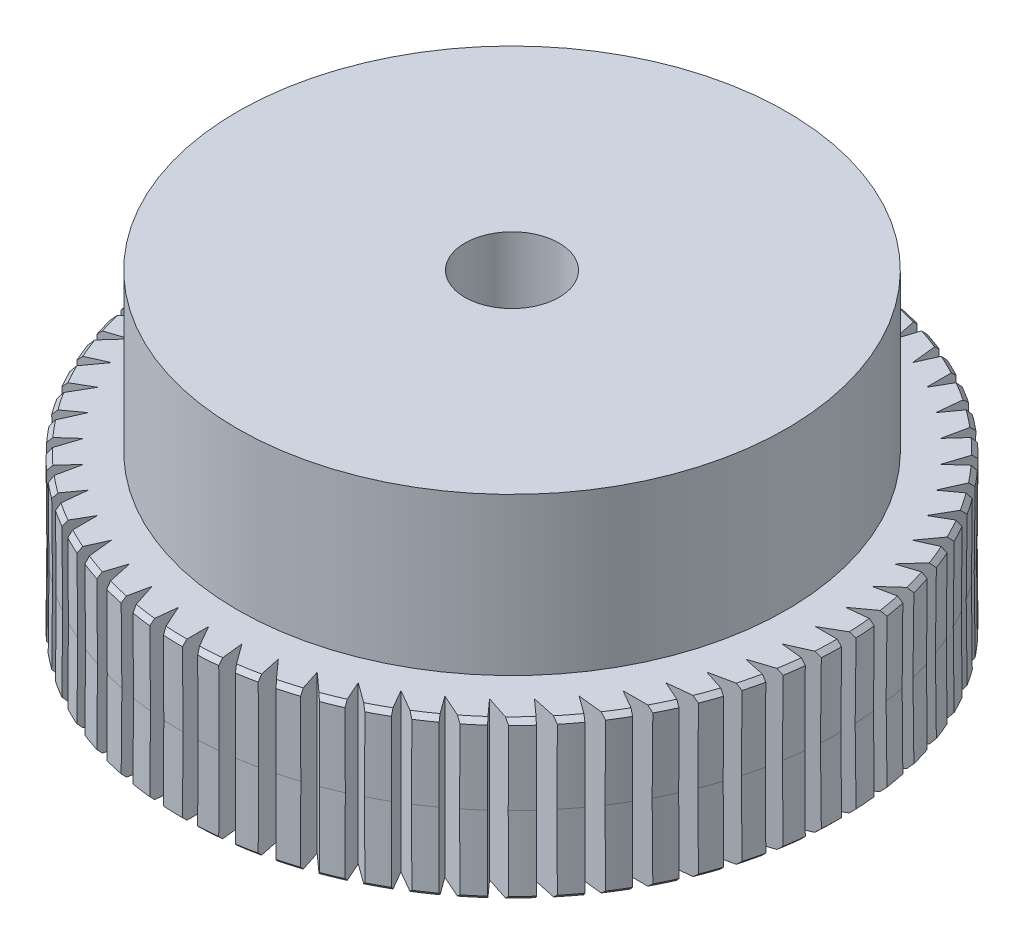
SolidWorks part; units mm, degrees
ref_plane "前视基准面" through (0, 0, 0) normal (0, 0, 1) x (1, 0, 0)
ref_plane "上视基准面" through (0, 0, 0) normal (0, 1, 0) x (1, 0, 0)
ref_plane "右视基准面" through (0, 0, 0) normal (1, 0, 0) x (0, 0, -1)
sketch "草图1" plane through (0, 0, 0) normal (0, 1, 0) x (1, 0, 0)
  circle A0 centre (0, 0) radius 21
  dimension "D1" = 42
extrude "凸台-拉伸1" add sketch "草图1" along normal blind 10
sketch "草图2" plane through (0, 10, 0) normal (0, 1, 0) x (1, 0, 0)
  circle A0 centre (0, 0) radius 17.5
  dimension "D1" = 35
extrude "凸台-拉伸2" add sketch "草图2" along normal blind 10
sketch "草图3" plane through (0, 10, 0) normal (0, 1, 0) x (1, 0, 0)
  line L0 (0, -21) -> (0, -19.3366)
  line L1 (0, -19.3366) -> (0.948, -20.9786)
  line L2 (-2.0212, -19.2306) -> (-1.25, -20.9628)
  line L3 (-2.1951, -20.885) -> (-2.0212, -19.2306)
  line L4 (-4.0203, -18.914) -> (-3.4344, -20.7173)
  line L5 (-4.3661, -20.5411) -> (-4.0203, -18.914)
  line L6 (-5.9753, -18.3902) -> (-5.5811, -20.2448)
  line L7 (-6.4894, -19.9722) -> (-5.9753, -18.3902)
  line L8 (-7.8649, -17.6648) -> (-7.6667, -19.5505)
  line L9 (-8.5415, -19.1845) -> (-7.8649, -17.6648)
  line L10 (-9.6683, -16.746) -> (-9.6683, -18.642)
  line L11 (-10.5, -18.1865) -> (-9.6683, -16.746)
  line L12 (-11.3657, -15.6436) -> (-11.5639, -17.5293)
  line L13 (-12.3435, -16.9894) -> (-11.3657, -15.6436)
  line L14 (-12.9387, -14.3699) -> (-13.3329, -16.2245)
  line L15 (-14.0517, -15.606) -> (-12.9387, -14.3699)
  line L16 (-14.3699, -12.9387) -> (-14.9558, -14.7419)
  line L17 (-15.606, -14.0517) -> (-14.3699, -12.9387)
  line L18 (-15.6436, -11.3657) -> (-16.4148, -13.0979)
  line L19 (-16.9894, -12.3435) -> (-15.6436, -11.3657)
  line L20 (-16.746, -9.6683) -> (-17.694, -11.3103)
  line L21 (-18.1865, -10.5) -> (-16.746, -9.6683)
  line L22 (-17.6648, -7.8649) -> (-18.7793, -9.3988)
  line L23 (-19.1845, -8.5415) -> (-17.6648, -7.8649)
  line L24 (-18.3902, -5.9753) -> (-19.6589, -7.3844)
  line L25 (-19.9722, -6.4894) -> (-18.3902, -5.9753)
  line L26 (-18.914, -4.0203) -> (-20.3231, -5.289)
  line L27 (-20.5411, -4.3661) -> (-18.914, -4.0203)
  line L28 (-19.2306, -2.0212) -> (-20.7646, -3.1357)
  line L29 (-20.885, -2.1951) -> (-19.2306, -2.0212)
  line L30 (-19.3366, 0) -> (-20.9786, -0.948)
  line L31 (-21, 0) -> (-19.3366, 0)
  line L32 (-19.2306, 2.0212) -> (-20.9628, 1.25)
  line L33 (-20.885, 2.1951) -> (-19.2306, 2.0212)
  line L34 (-18.914, 4.0203) -> (-20.7173, 3.4344)
  line L35 (-20.5411, 4.3661) -> (-18.914, 4.0203)
  line L36 (-18.3902, 5.9753) -> (-20.2448, 5.5811)
  line L37 (-19.9722, 6.4894) -> (-18.3902, 5.9753)
  line L38 (-17.6648, 7.8649) -> (-19.5505, 7.6667)
  line L39 (-19.1845, 8.5415) -> (-17.6648, 7.8649)
  line L40 (-16.746, 9.6683) -> (-18.642, 9.6683)
  line L41 (-18.1865, 10.5) -> (-16.746, 9.6683)
  line L42 (-15.6436, 11.3657) -> (-17.5293, 11.5639)
  line L43 (-16.9894, 12.3435) -> (-15.6436, 11.3657)
  line L44 (-14.3699, 12.9387) -> (-16.2245, 13.3329)
  line L45 (-15.606, 14.0517) -> (-14.3699, 12.9387)
  line L46 (-12.9387, 14.3699) -> (-14.7419, 14.9558)
  line L47 (-14.0517, 15.606) -> (-12.9387, 14.3699)
  line L48 (-11.3657, 15.6436) -> (-13.0979, 16.4148)
  line L49 (-12.3435, 16.9894) -> (-11.3657, 15.6436)
  line L50 (-9.6683, 16.746) -> (-11.3103, 17.694)
  line L51 (-10.5, 18.1865) -> (-9.6683, 16.746)
  line L52 (-7.8649, 17.6648) -> (-9.3988, 18.7793)
  line L53 (-8.5415, 19.1845) -> (-7.8649, 17.6648)
  line L54 (-5.9753, 18.3902) -> (-7.3844, 19.6589)
  line L55 (-6.4894, 19.9722) -> (-5.9753, 18.3902)
  line L56 (-4.0203, 18.914) -> (-5.289, 20.3231)
  line L57 (-4.3661, 20.5411) -> (-4.0203, 18.914)
  line L58 (-2.0212, 19.2306) -> (-3.1357, 20.7646)
  line L59 (-2.1951, 20.885) -> (-2.0212, 19.2306)
  line L60 (0, 19.3366) -> (-0.948, 20.9786)
  line L61 (0, 21) -> (0, 19.3366)
  line L62 (2.0212, 19.2306) -> (1.25, 20.9628)
  line L63 (2.1951, 20.885) -> (2.0212, 19.2306)
  line L64 (4.0203, 18.914) -> (3.4344, 20.7173)
  line L65 (4.3661, 20.5411) -> (4.0203, 18.914)
  line L66 (5.9753, 18.3902) -> (5.5811, 20.2448)
  line L67 (6.4894, 19.9722) -> (5.9753, 18.3902)
  line L68 (7.8649, 17.6648) -> (7.6667, 19.5505)
  line L69 (8.5415, 19.1845) -> (7.8649, 17.6648)
  line L70 (9.6683, 16.746) -> (9.6683, 18.642)
  line L71 (10.5, 18.1865) -> (9.6683, 16.746)
  line L72 (11.3657, 15.6436) -> (11.5639, 17.5293)
  line L73 (12.3435, 16.9894) -> (11.3657, 15.6436)
  line L74 (12.9387, 14.3699) -> (13.3329, 16.2245)
  line L75 (14.0517, 15.606) -> (12.9387, 14.3699)
  line L76 (14.3699, 12.9387) -> (14.9558, 14.7419)
  line L77 (15.606, 14.0517) -> (14.3699, 12.9387)
  line L78 (15.6436, 11.3657) -> (16.4148, 13.0979)
  line L79 (16.9894, 12.3435) -> (15.6436, 11.3657)
  line L80 (16.746, 9.6683) -> (17.694, 11.3103)
  line L81 (18.1865, 10.5) -> (16.746, 9.6683)
  line L82 (17.6648, 7.8649) -> (18.7793, 9.3988)
  line L83 (19.1845, 8.5415) -> (17.6648, 7.8649)
  line L84 (18.3902, 5.9753) -> (19.6589, 7.3844)
  line L85 (19.9722, 6.4894) -> (18.3902, 5.9753)
  line L86 (18.914, 4.0203) -> (20.3231, 5.289)
  line L87 (20.5411, 4.3661) -> (18.914, 4.0203)
  line L88 (19.2306, 2.0212) -> (20.7646, 3.1357)
  line L89 (20.885, 2.1951) -> (19.2306, 2.0212)
  line L90 (19.3366, 0) -> (20.9786, 0.948)
  line L91 (21, 0) -> (19.3366, 0)
  line L92 (19.2306, -2.0212) -> (20.9628, -1.25)
  line L93 (20.885, -2.1951) -> (19.2306, -2.0212)
  line L94 (18.914, -4.0203) -> (20.7173, -3.4344)
  line L95 (20.5411, -4.3661) -> (18.914, -4.0203)
  line L96 (18.3902, -5.9753) -> (20.2448, -5.5811)
  line L97 (19.9722, -6.4894) -> (18.3902, -5.9753)
  line L98 (17.6648, -7.8649) -> (19.5505, -7.6667)
  line L99 (19.1845, -8.5415) -> (17.6648, -7.8649)
  line L100 (16.746, -9.6683) -> (18.642, -9.6683)
  line L101 (18.1865, -10.5) -> (16.746, -9.6683)
  line L102 (15.6436, -11.3657) -> (17.5293, -11.5639)
  line L103 (16.9894, -12.3435) -> (15.6436, -11.3657)
  line L104 (14.3699, -12.9387) -> (16.2245, -13.3329)
  line L105 (15.606, -14.0517) -> (14.3699, -12.9387)
  line L106 (12.9387, -14.3699) -> (14.7419, -14.9558)
  line L107 (14.0517, -15.606) -> (12.9387, -14.3699)
  line L108 (11.3657, -15.6436) -> (13.0979, -16.4148)
  line L109 (12.3435, -16.9894) -> (11.3657, -15.6436)
  line L110 (9.6683, -16.746) -> (11.3103, -17.694)
  line L111 (10.5, -18.1865) -> (9.6683, -16.746)
  line L112 (7.8649, -17.6648) -> (9.3988, -18.7793)
  line L113 (8.5415, -19.1845) -> (7.8649, -17.6648)
  line L114 (5.9753, -18.3902) -> (7.3844, -19.6589)
  line L115 (6.4894, -19.9722) -> (5.9753, -18.3902)
  line L116 (4.0203, -18.914) -> (5.289, -20.3231)
  line L117 (4.3661, -20.5411) -> (4.0203, -18.914)
  line L118 (2.0212, -19.2306) -> (3.1357, -20.7646)
  line L119 (2.1951, -20.885) -> (2.0212, -19.2306)
  circle A0 centre (0, 0) radius 21 construction
  arc A1 (0, -21) -> (0.948, -20.9786) centre (0, 0) ccw
  arc A2 (-2.1951, -20.885) -> (-1.25, -20.9628) centre (0, 0) ccw
  arc A3 (-4.3661, -20.5411) -> (-3.4344, -20.7173) centre (0, 0) ccw
  arc A4 (-6.4894, -19.9722) -> (-5.5811, -20.2448) centre (0, 0) ccw
  arc A5 (-8.5415, -19.1845) -> (-7.6667, -19.5505) centre (0, 0) ccw
  arc A6 (-10.5, -18.1865) -> (-9.6683, -18.642) centre (0, 0) ccw
  arc A7 (-12.3435, -16.9894) -> (-11.5639, -17.5293) centre (0, 0) ccw
  arc A8 (-14.0517, -15.606) -> (-13.3329, -16.2245) centre (0, 0) ccw
  arc A9 (-15.606, -14.0517) -> (-14.9558, -14.7419) centre (0, 0) ccw
  arc A10 (-16.9894, -12.3435) -> (-16.4148, -13.0979) centre (0, 0) ccw
  arc A11 (-18.1865, -10.5) -> (-17.694, -11.3103) centre (0, 0) ccw
  arc A12 (-19.1845, -8.5415) -> (-18.7793, -9.3988) centre (0, 0) ccw
  arc A13 (-19.9722, -6.4894) -> (-19.6589, -7.3844) centre (0, 0) ccw
  arc A14 (-20.5411, -4.3661) -> (-20.3231, -5.289) centre (0, 0) ccw
  arc A15 (-20.885, -2.1951) -> (-20.7646, -3.1357) centre (0, 0) ccw
  arc A16 (-21, 0) -> (-20.9786, -0.948) centre (0, 0) ccw
  arc A17 (-20.885, 2.1951) -> (-20.9628, 1.25) centre (0, 0) ccw
  arc A18 (-20.5411, 4.3661) -> (-20.7173, 3.4344) centre (0, 0) ccw
  arc A19 (-19.9722, 6.4894) -> (-20.2448, 5.5811) centre (0, 0) ccw
  arc A20 (-19.1845, 8.5415) -> (-19.5505, 7.6667) centre (0, 0) ccw
  arc A21 (-18.1865, 10.5) -> (-18.642, 9.6683) centre (0, 0) ccw
  arc A22 (-16.9894, 12.3435) -> (-17.5293, 11.5639) centre (0, 0) ccw
  arc A23 (-15.606, 14.0517) -> (-16.2245, 13.3329) centre (0, 0) ccw
  arc A24 (-14.0517, 15.606) -> (-14.7419, 14.9558) centre (0, 0) ccw
  arc A25 (-12.3435, 16.9894) -> (-13.0979, 16.4148) centre (0, 0) ccw
  arc A26 (-10.5, 18.1865) -> (-11.3103, 17.694) centre (0, 0) ccw
  arc A27 (-8.5415, 19.1845) -> (-9.3988, 18.7793) centre (0, 0) ccw
  arc A28 (-6.4894, 19.9722) -> (-7.3844, 19.6589) centre (0, 0) ccw
  arc A29 (-4.3661, 20.5411) -> (-5.289, 20.3231) centre (0, 0) ccw
  arc A30 (-2.1951, 20.885) -> (-3.1357, 20.7646) centre (0, 0) ccw
  arc A31 (0, 21) -> (-0.948, 20.9786) centre (0, 0) ccw
  arc A32 (2.1951, 20.885) -> (1.25, 20.9628) centre (0, 0) ccw
  arc A33 (4.3661, 20.5411) -> (3.4344, 20.7173) centre (0, 0) ccw
  arc A34 (6.4894, 19.9722) -> (5.5811, 20.2448) centre (0, 0) ccw
  arc A35 (8.5415, 19.1845) -> (7.6667, 19.5505) centre (0, 0) ccw
  arc A36 (10.5, 18.1865) -> (9.6683, 18.642) centre (0, 0) ccw
  arc A37 (12.3435, 16.9894) -> (11.5639, 17.5293) centre (0, 0) ccw
  arc A38 (14.0517, 15.606) -> (13.3329, 16.2245) centre (0, 0) ccw
  arc A39 (15.606, 14.0517) -> (14.9558, 14.7419) centre (0, 0) ccw
  arc A40 (16.9894, 12.3435) -> (16.4148, 13.0979) centre (0, 0) ccw
  arc A41 (18.1865, 10.5) -> (17.694, 11.3103) centre (0, 0) ccw
  arc A42 (19.1845, 8.5415) -> (18.7793, 9.3988) centre (0, 0) ccw
  arc A43 (19.9722, 6.4894) -> (19.6589, 7.3844) centre (0, 0) ccw
  arc A44 (20.5411, 4.3661) -> (20.3231, 5.289) centre (0, 0) ccw
  arc A45 (20.885, 2.1951) -> (20.7646, 3.1357) centre (0, 0) ccw
  arc A46 (21, 0) -> (20.9786, 0.948) centre (0, 0) ccw
  arc A47 (20.885, -2.1951) -> (20.9628, -1.25) centre (0, 0) ccw
  arc A48 (20.5411, -4.3661) -> (20.7173, -3.4344) centre (0, 0) ccw
  arc A49 (19.9722, -6.4894) -> (20.2448, -5.5811) centre (0, 0) ccw
  arc A50 (19.1845, -8.5415) -> (19.5505, -7.6667) centre (0, 0) ccw
  arc A51 (18.1865, -10.5) -> (18.642, -9.6683) centre (0, 0) ccw
  arc A52 (16.9894, -12.3435) -> (17.5293, -11.5639) centre (0, 0) ccw
  arc A53 (15.606, -14.0517) -> (16.2245, -13.3329) centre (0, 0) ccw
  arc A54 (14.0517, -15.606) -> (14.7419, -14.9558) centre (0, 0) ccw
  arc A55 (12.3435, -16.9894) -> (13.0979, -16.4148) centre (0, 0) ccw
  arc A56 (10.5, -18.1865) -> (11.3103, -17.694) centre (0, 0) ccw
  arc A57 (8.5415, -19.1845) -> (9.3988, -18.7793) centre (0, 0) ccw
  arc A58 (6.4894, -19.9722) -> (7.3844, -19.6589) centre (0, 0) ccw
  arc A59 (4.3661, -20.5411) -> (5.289, -20.3231) centre (0, 0) ccw
  arc A60 (2.1951, -20.885) -> (3.1357, -20.7646) centre (0, 0) ccw
  point P187 (0, 0)
  dimension "D1" = 30
  dimension "D2" = 60
extrude "切除-拉伸1" cut sketch "草图3" against normal blind 35
sketch "草图4" plane through (0, 20, 0) normal (0, 1, 0) x (1, 0, 0)
  circle A0 centre (0, 0) radius 3
  dimension "D1" = 6
extrude "切除-拉伸2" cut sketch "草图4" against normal through all
sketch "草图6" plane through (0, 0, 0) normal (1, 0, 0) x (0, 0, -1)
  line L0 (18.642, 5) -> (30.3114, 5) construction
  line L1 (18.642, 0) -> (18.642, 10) construction
  line L2 (20.7173, 10) -> (21, 9.7173)
  line L3 (21, 0) -> (21, 10) construction
  line L4 (21, 9.7173) -> (20.9628, 5)
  line L5 (20.9628, 0) -> (20.9628, 10) construction
  line L6 (21, 0.2827) -> (20.9628, 5)
  line L7 (20.7173, 0) -> (21, 0.2827)
  line L8 (20.7173, 10) -> (24.5195, 10)
  line L9 (24.5195, 10) -> (24.5195, 0)
  line L10 (24.5195, 0) -> (20.7173, 0)
  line L11 (0, 0) -> (0, 29.0671) construction
revolve "切除-旋转1" cut sketch "草图6" angle 360 about L11
